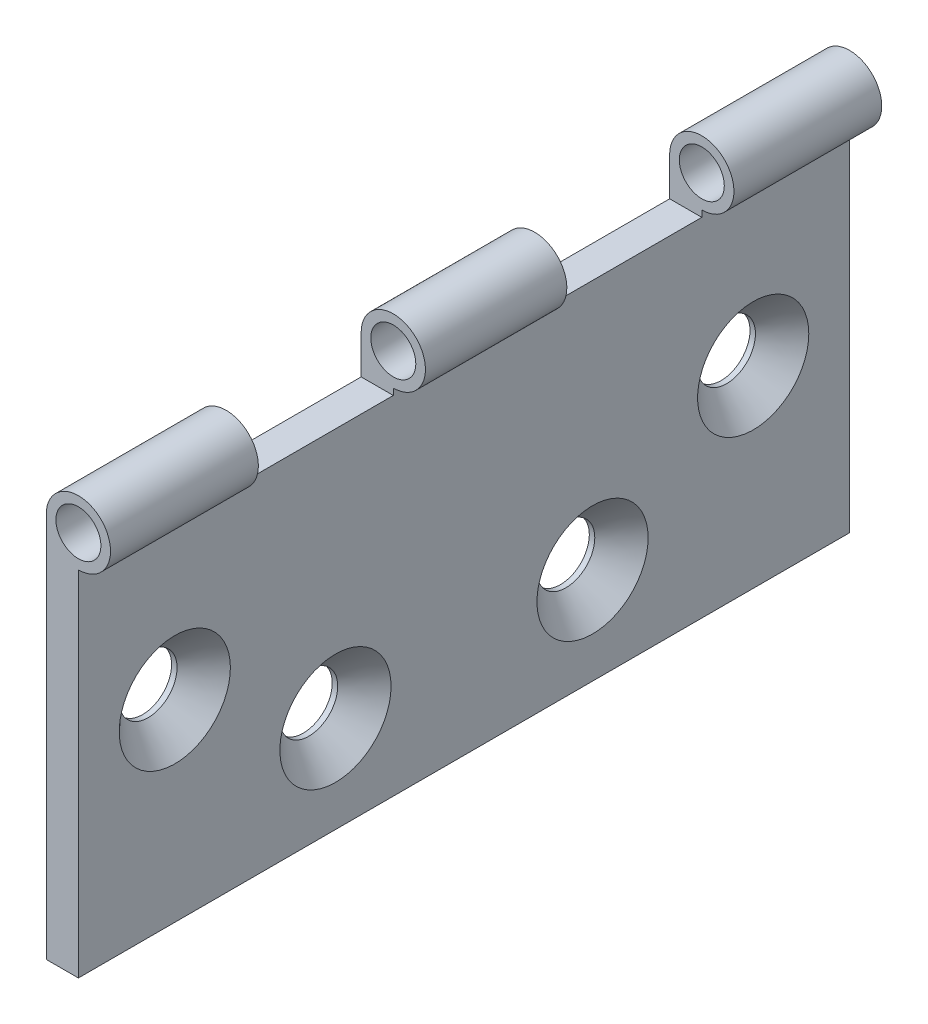
SolidWorks part; units mm, degrees
ref_plane "Front" through (0, 0, 0) normal (0, 0, 1) x (1, 0, 0)
ref_plane "Top" through (0, 0, 0) normal (0, 1, 0) x (1, 0, 0)
ref_plane "Right" through (0, 0, 0) normal (1, 0, 0) x (0, 0, -1)
sketch "草图1" plane through (0, 0, 0) normal (0, 0, 1) x (1, 0, 0)
  line L0 (0, 0) -> (0, 60)
  dimension "D1" = 60
extrude "拉伸-薄壁1" add sketch "草图1" along normal mid plane 120 thin
sketch "草图2" plane through (0, 0, 60) normal (0, 0, 1) x (1, 0, 0)
  circle A0 centre (5, 60) radius 5
sweep "扫描1" add profiles "草图2" path edge at (5, 60, 0)
sketch "草图3" plane through (0, 0, 60) normal (0, 0, 1) x (1, 0, 0)
  circle A0 centre (5, 60) radius 3.5
  dimension "D1" = 7
extrude "切除-拉伸1" cut sketch "草图3" against normal through all
hole_wizard "M8 平头机械螺钉的锥形沉头孔1" positions "孔定位" profile "草图5" countersink size "M8" standard "ANSI Metric" end condition through all
sketch "孔定位" plane through (5, 0, 0) normal (1, 0, 0) x (0, 0, -1)
  line L0 (-60, 0) -> (60, 0) construction
  point P0 (-45, 30)
  point P2 (-20, 15)
  dimension "D1" = 30
  dimension "D2" = 15
  dimension "D3" = 40
  dimension "D4" = 15
sketch "草图5" plane through (5, 30, 45) normal (0, 1, 0) x (0, 0, -1)
  line L0 (0, 0) -> (0, 5)
  line L1 (0, 5) -> (4.5, 5)
  line L2 (4.5, 5) -> (4.5, 4.15)
  line L3 (4.5, 4.15) -> (8.65, 0)
  line L5 (8.65, 0) -> (0, 0)
  line L6 (-4.5, 4.15) -> (-8.65, 0) construction
  line L11 (0, -6.35) -> (0, 107.95) construction
  dimension "通孔孔直径" = 9
  dimension "通孔孔深度" = 5
  dimension "近端锥形沉头孔直径" = 17.3
  dimension "近端锥形沉头孔角度" = 90
mirror "镜向1" about plane through (0, 0, 0) normal (0, 0, 1) of "M8 平头机械螺钉的锥形沉头孔1"
sketch "切除布局" plane through (5, 0, 0) normal (1, 0, 0) x (0, 0, -1)
  line L2 (60, 60) -> (60, 65) construction
  line L3 (-60, 54) -> (60, 54)
  line L4 (-60, 54) -> (60, 54)
  line L5 (-60, 65) -> (-60, 60) construction
  line L6 (60, 54) -> (60, 65)
  line L7 (-60, 65) -> (-60, 54)
  line L8 (-60, 65) -> (60, 65)
  line L9 (-36, 65) -> (-36, 55.3577)
  line L10 (-12, 65) -> (-12, 55.3577)
  line L11 (0, 0) -> (0, 79.2162) construction
  line L12 (12, 65) -> (12, 55.3577)
  line L13 (36, 65) -> (36, 55.3577)
  point P10 (-36, 60.1788)
  dimension "D2" = 24
  dimension "D3" = 24
  dimension "D1" = 1
sketch "草图11" plane through (5, 0, 0) normal (1, 0, 0) x (0, 0, -1)
  line L0 (-60, 54) -> (60, 54) construction
  line L2 (-60, 65) -> (60, 65) construction
  line L5 (-37, 65) -> (-11, 65)
  line L7 (-37, 54) -> (-11, 54)
  line L8 (11, 65) -> (37, 65)
  line L11 (-37, 65) -> (-37, 55.3577)
  line L12 (-37, 65) -> (-37, 54)
  line L14 (-11, 65) -> (-11, 55.3577)
  line L15 (-11, 65) -> (-11, 54)
  line L17 (11, 65) -> (11, 55.3577)
  line L18 (11, 65) -> (11, 54)
  line L19 (11, 54) -> (37, 54)
  line L20 (37, 65) -> (37, 55.3577)
  line L21 (37, 65) -> (37, 54)
  dimension "D1" = 1
  dimension "D2" = 1
  dimension "D3" = 1
  dimension "D4" = 1
extrude "两处切除" cut sketch "草图11" against normal through all and the other way through all
sketch "草图8" plane through (5, 0, 0) normal (1, 0, 0) x (0, 0, -1)
  line L0 (-60, 54) -> (60, 54) construction
  line L1 (60, 54) -> (60, 65) construction
  line L2 (-60, 65) -> (60, 65) construction
  line L3 (-60, 65) -> (-60, 54) construction
  line L4 (60, 55) -> (37, 55)
  line L5 (-60, 55) -> (-60, 0)
  line L6 (-60, 0) -> (60, 0)
  line L7 (60, 0) -> (60, 55)
  line L8 (60, 55) -> (37, 55)
  line L9 (-60, 55) -> (-60, 0)
  line L10 (-60, 0) -> (60, 0)
  line L11 (60, 0) -> (60, 55)
  line L12 (-60, 54) -> (-35, 54)
  line L13 (60, 54) -> (60, 65)
  line L14 (-60, 65) -> (-35, 65)
  line L15 (-60, 65) -> (-60, 54)
  line L18 (-35, 65) -> (-35, 55.3577)
  line L19 (-35, 65) -> (-35, 54)
  line L21 (35, 65) -> (35, 55.3577)
  line L22 (35, 65) -> (35, 54)
  line L24 (-13, 65) -> (-13, 55.3577)
  line L25 (-13, 65) -> (-13, 54)
  line L26 (-13, 65) -> (13, 65)
  line L27 (13, 65) -> (13, 55.3577)
  line L28 (13, 65) -> (13, 54)
  line L29 (35, 65) -> (60, 65)
  line L30 (-13, 54) -> (13, 54)
  line L31 (35, 54) -> (60, 54)
  line L40 (-11, 54) -> (-37, 54)
  line L41 (-11, 54) -> (-37, 54)
  line L42 (-37, 54) -> (-37, 55)
  line L43 (-37, 54) -> (-37, 55)
  line L44 (-37, 55) -> (-60, 55)
  line L45 (-37, 55) -> (-60, 55)
  line L46 (37, 55) -> (37, 54)
  line L47 (37, 55) -> (37, 54)
  line L48 (37, 54) -> (11, 54)
  line L49 (37, 54) -> (11, 54)
  line L50 (11, 54) -> (11, 55)
  line L51 (11, 54) -> (11, 55)
  line L52 (11, 55) -> (-11, 55)
  line L53 (11, 55) -> (-11, 55)
  line L54 (-11, 55) -> (-11, 54)
  line L55 (-11, 55) -> (-11, 54)
  dimension "D1" = 0
  dimension "D2" = 1
  dimension "D3" = 1
  dimension "D4" = 1
  dimension "D5" = 1
extrude "切除-拉伸2" [suppressed] cut sketch "草图8" against normal through all and the other way through all contours L14 L19 L12 L15 | L26 L28 L30 L25 | L29 L13 L31 L22
equation "\"D1@孔定位\"= \"D1@草图1\" / 2"
equation "\"D3@孔定位\"= \"D1@拉伸-薄壁1\" / 3"
equation "\"D2@切除布局\"= \"D1@拉伸-薄壁1\" / 5"
equation "\"D3@切除布局\"= \"D1@拉伸-薄壁1\" / 5"
